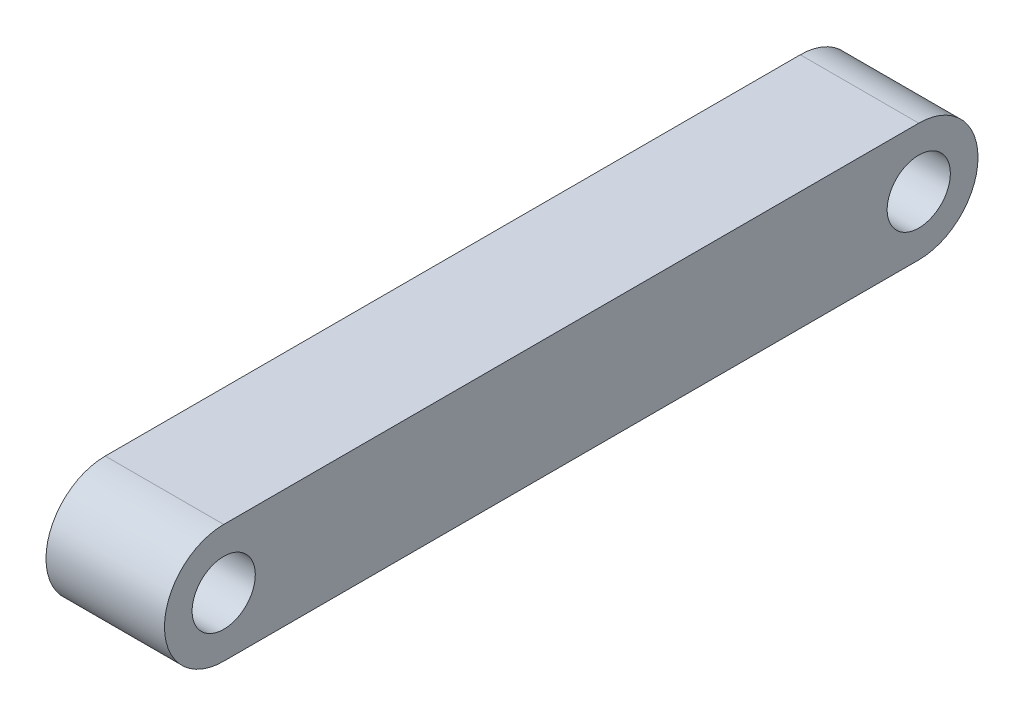
SolidWorks part; units mm, degrees
ref_plane "Front Plane" through (0, 0, 0) normal (0, 0, 1) x (1, 0, 0)
ref_plane "Top Plane" through (0, 0, 0) normal (0, 1, 0) x (1, 0, 0)
ref_plane "Right Plane" through (0, 0, 0) normal (1, 0, 0) x (0, 0, -1)
sketch "Sketch1" plane through (0, 0, 0) normal (1, 0, 0) x (0, 0, -1)
  line L0 (-44, 0) -> (44, 0) construction
  line L1 (-44, 7.5) -> (44, 7.5)
  line L2 (-44, -7.5) -> (44, -7.5)
  arc A0 (-44, 7.5) -> (-44, -7.5) centre (-44, 0) ccw
  arc A1 (44, -7.5) -> (44, 7.5) centre (44, 0) ccw
  circle A2 centre (-44, 0) radius 4
  circle A3 centre (44, 0) radius 4
  point P2 (0, 0)
  dimension "D1" = 8
  dimension "D2" = 8
  dimension "D3" = 15
  dimension "D4" = 88
extrude "Boss-Extrude1" add sketch "Sketch1" along normal mid plane 15
